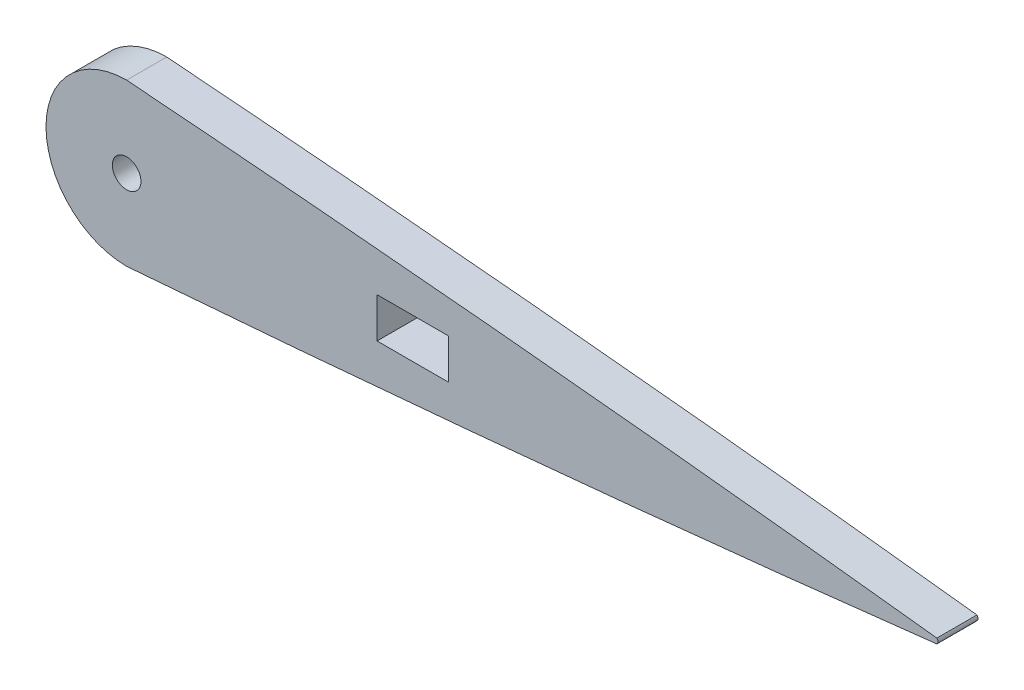
SolidWorks part; units mm, degrees
material "Фанера"
ref_plane "Front Plane" through (0, 0, 0) normal (0, 0, 1) x (1, 0, 0)
ref_plane "Top Plane" through (0, 0, 0) normal (0, 1, 0) x (1, 0, 0)
ref_plane "Right Plane" through (0, 0, 0) normal (1, 0, 0) x (0, 0, -1)
curve "Кривая1"
  spline degree 3 poles (110, 0, 0) (110.0276, -0.2367, 0) (110.0855, -0.7342, 0) (110.5302, -1.4271, 0) (111.1963, -2.0786, 0) (112.1098, -2.7013, 0) (113.2568, -3.2993, 0) (114.6379, -3.8731, 0) (116.2477, -4.4214, 0) (118.0813, -4.9426, 0) (120.1331, -5.4348, 0) (122.3972, -5.8961, 0) (124.8672, -6.3247, 0) (127.537, -6.7187, 0) (130.3997, -7.0764, 0) (133.4488, -7.3965, 0) (136.6771, -7.6776, 0) (140.0777, -7.9187, 0) (143.6433, -8.119, 0) (147.3662, -8.278, 0) (151.2389, -8.3955, 0) (155.2534, -8.4715, 0) (159.4016, -8.5065, 0) (163.6751, -8.501, 0) (168.0653, -8.456, 0) (172.5632, -8.3725, 0) (177.1595, -8.252, 0) (181.8446, -8.096, 0) (186.6087, -7.9062, 0) (191.4413, -7.6846, 0) (196.3316, -7.4331, 0) (201.2684, -7.1538, 0) (206.2396, -6.8489, 0) (211.233, -6.5205, 0) (216.2352, -6.1709, 0) (221.2323, -5.8022, 0) (226.2093, -5.417, 0) (231.1504, -5.0174, 0) (236.0382, -4.6058, 0) (240.8542, -4.1849, 0) (245.5777, -3.7574, 0) (250.1862, -3.3262, 0) (254.6542, -2.8948, 0) (258.9526, -2.4672, 0) (263.0477, -2.0479, 0) (266.899, -1.6426, 0) (270.4558, -1.2586, 0) (273.6512, -0.9053, 0) (276.3854, -0.5964, 0) (278.4526, -0.359, 0) (279.592, -0.2261, 0) (280, -0.1785, 0) knots 0 0 0 0 0.004099 0.008615 0.013935 0.020278 0.027753 0.03641 0.046266 0.05732 0.069559 0.082963 0.097507 0.113164 0.129903 0.14769 0.166492 0.186272 0.206992 0.228612 0.251092 0.274389 0.298458 0.323254 0.348728 0.37483 0.401509 0.42871 0.456376 0.484448 0.512864 0.541558 0.570462 0.599504 0.628607 0.65769 0.686667 0.715445 0.743924 0.771995 0.79954 0.826428 0.852512 0.877624 0.901571 0.924121 0.944989 0.963804 0.980044 0.992855 1 1 1 1
curve "Кривая2"
  spline degree 3 poles (280, 0.1785, 0) (279.592, 0.2261, 0) (278.4526, 0.359, 0) (276.3854, 0.5964, 0) (273.6512, 0.9053, 0) (270.4558, 1.2586, 0) (266.899, 1.6426, 0) (263.0477, 2.0479, 0) (258.9526, 2.4672, 0) (254.6542, 2.8948, 0) (250.1862, 3.3262, 0) (245.5777, 3.7574, 0) (240.8542, 4.1849, 0) (236.0382, 4.6058, 0) (231.1504, 5.0174, 0) (226.2093, 5.417, 0) (221.2323, 5.8022, 0) (216.2352, 6.1709, 0) (211.233, 6.5205, 0) (206.2396, 6.8489, 0) (201.2684, 7.1538, 0) (196.3316, 7.4331, 0) (191.4413, 7.6846, 0) (186.6087, 7.9062, 0) (181.8446, 8.096, 0) (177.1595, 8.252, 0) (172.5632, 8.3725, 0) (168.0653, 8.456, 0) (163.6751, 8.501, 0) (159.4016, 8.5065, 0) (155.2534, 8.4715, 0) (151.2389, 8.3955, 0) (147.3662, 8.278, 0) (143.6433, 8.119, 0) (140.0777, 7.9187, 0) (136.6771, 7.6776, 0) (133.4488, 7.3965, 0) (130.3997, 7.0764, 0) (127.537, 6.7187, 0) (124.8672, 6.3247, 0) (122.3972, 5.8961, 0) (120.1331, 5.4348, 0) (118.0813, 4.9426, 0) (116.2477, 4.4214, 0) (114.6379, 3.8731, 0) (113.2568, 3.2993, 0) (112.1098, 2.7013, 0) (111.1963, 2.0786, 0) (110.5302, 1.4271, 0) (110.0855, 0.7342, 0) (110.0276, 0.2367, 0) (110, 0, 0) knots 0 0 0 0 0.007145 0.019956 0.036196 0.055011 0.075879 0.098429 0.122376 0.147488 0.173572 0.20046 0.228005 0.256076 0.284555 0.313333 0.34231 0.371393 0.400496 0.429538 0.458442 0.487136 0.515552 0.543624 0.57129 0.598491 0.62517 0.651272 0.676746 0.701542 0.725611 0.748908 0.771388 0.793008 0.813728 0.833508 0.85231 0.870097 0.886836 0.902493 0.917037 0.930441 0.94268 0.953734 0.96359 0.972247 0.979722 0.986065 0.991385 0.995901 1 1 1 1
sketch "Эскиз1" plane through (0, 0, 0) normal (0, 0, 1) x (1, 0, 0)
  line L0 (105.1708, 0) -> (280.7263, 0) construction
  line L1 (280.0739, 0) -> (280.0739, 24.3846) construction
  line L2 (110, -5.3315) -> (110, 17.5304) construction
  line L3 (152.5185, 18.8331) -> (152.5185, -21.3473) construction
  line L4 (223.3826, 13.2402) -> (223.3826, -18.4275) construction
  line L5 (217.7476, 6.0581) -> (217.7476, -6.0581)
  line L6 (127.0185, -3) -> (140.0185, -3)
  line L7 (125.0185, -1) -> (125.0185, 1)
  line L8 (127.0185, 3) -> (140.0185, 3)
  line L9 (142.0185, -1) -> (142.0185, 1)
  line L10 (125.0185, -3) -> (142.0185, 3) construction
  line L11 (125.0185, 3) -> (142.0185, -3) construction
  line L12 (165.0185, -4.5) -> (185.0185, -4.5)
  line L13 (163.0185, -2.5) -> (163.0185, 2.5)
  line L14 (165.0185, 4.5) -> (185.0185, 4.5)
  line L15 (187.0185, -2.5) -> (187.0185, 2.5)
  line L16 (163.0185, -4.5) -> (187.0185, 4.5) construction
  line L17 (163.0185, 4.5) -> (187.0185, -4.5) construction
  line L18 (243.3826, 16.1127) -> (243.3826, -19.2013) construction
  line L19 (240.8826, -1.4) -> (245.8826, -1.4)
  line L20 (240.8826, -1.4) -> (240.8826, 1.4)
  line L21 (240.8826, 1.4) -> (245.8826, 1.4)
  line L22 (245.8826, -1.4) -> (245.8826, 1.4)
  line L23 (240.8826, -1.4) -> (245.8826, 1.4) construction
  line L24 (240.8826, 1.4) -> (245.8826, -1.4) construction
  arc A0 (280, 0.1785) -> (280, -0.1785) centre (279.8215, 0) cw
  circle A1 centre (152.5185, 0) radius 4
  circle A2 centre (197.5185, 0) radius 4
  arc A3 (185.0185, 4.5) -> (187.0185, 2.5) centre (185.0185, 2.5) cw
  arc A4 (185.0185, -4.5) -> (187.0185, -2.5) centre (185.0185, -2.5) ccw
  arc A5 (165.0185, -4.5) -> (163.0185, -2.5) centre (165.0185, -2.5) cw
  arc A6 (163.0185, 2.5) -> (165.0185, 4.5) centre (165.0185, 2.5) cw
  arc A7 (125.0185, 1) -> (127.0185, 3) centre (127.0185, 1) cw
  arc A8 (127.0185, -3) -> (125.0185, -1) centre (127.0185, -1) cw
  arc A9 (140.0185, -3) -> (142.0185, -1) centre (140.0185, -1) ccw
  arc A10 (140.0185, 3) -> (142.0185, 1) centre (140.0185, 1) cw
  arc A11 (223.3826, 5.635) -> (223.3826, -5.635) centre (223.3826, 0) ccw
  circle A12 centre (223.3826, 0) radius 1
  spline S0 degree 3 poles (-1802.3351, -584.8827) (164.5267, 33.7772) (105.6543, 6.1699) (110.5302, -1.4271) (111.1963, -2.0786) (112.1098, -2.7013) (113.2568, -3.2993) (114.6379, -3.8731) (116.2477, -4.4214) (118.0813, -4.9426) (120.1331, -5.4348) (122.3972, -5.8961) (124.8672, -6.3247) (127.537, -6.7187) (130.3997, -7.0764) (133.4488, -7.3965) (136.6771, -7.6776) (140.0777, -7.9187) (143.6433, -8.119) (147.3662, -8.278) (151.2389, -8.3955) (155.2534, -8.4715) (159.4016, -8.5065) (163.6751, -8.501) (168.0653, -8.456) (172.5632, -8.3725) (177.1595, -8.252) (181.8446, -8.096) (186.6087, -7.9062) (191.4413, -7.6846) (196.3316, -7.4331) (201.2684, -7.1538) (206.2396, -6.8489) (211.233, -6.5205) (216.2352, -6.1709) (221.2323, -5.8022) (226.2093, -5.417) (231.1504, -5.0174) (236.0382, -4.6058) (240.8542, -4.1849) (247.0711, -3.6222) (253.1161, -3.0479) (258.9526, -2.4672) (263.0477, -2.0479) (266.899, -1.6426) (270.4558, -1.2586) (273.6512, -0.9053) (276.3854, -0.5964) (359.5279, 8.955) (440.5611, 28.5776) (751.5392, -1938.3855) knots -0.13886 -0.13886 -0.13886 -0.13886 0.004099 0.008615 0.013935 0.020278 0.027753 0.03641 0.046266 0.05732 0.069559 0.082963 0.097507 0.113164 0.129903 0.14769 0.166492 0.186272 0.206992 0.228612 0.251092 0.274389 0.298458 0.323254 0.348728 0.37483 0.401509 0.42871 0.456376 0.484448 0.512864 0.541558 0.570462 0.599504 0.628607 0.65769 0.686667 0.715445 0.743924 0.771995 0.79954 0.852512 0.877624 0.901571 0.924121 0.944989 0.963804 0.980044 0.992855 2.419626 2.419626 2.419626 2.419626 only from (110, 0) to (280, -0.1785) construction
  spline S1 degree 3 poles (751.5383, 1938.3796) (440.561, -28.5775) (359.5279, -8.955) (276.3854, 0.5964) (273.6512, 0.9053) (270.4558, 1.2586) (266.899, 1.6426) (263.0477, 2.0479) (258.9526, 2.4672) (253.1161, 3.0479) (247.0711, 3.6222) (240.8542, 4.1849) (236.0382, 4.6058) (231.1504, 5.0174) (226.2093, 5.417) (221.2323, 5.8022) (216.2352, 6.1709) (211.233, 6.5205) (206.2396, 6.8489) (201.2684, 7.1538) (196.3316, 7.4331) (191.4413, 7.6846) (186.6087, 7.9062) (181.8446, 8.096) (177.1595, 8.252) (172.5632, 8.3725) (168.0653, 8.456) (163.6751, 8.501) (159.4016, 8.5065) (155.2534, 8.4715) (151.2389, 8.3955) (147.3662, 8.278) (143.6433, 8.119) (140.0777, 7.9187) (136.6771, 7.6776) (133.4488, 7.3965) (130.3997, 7.0764) (127.537, 6.7187) (124.8672, 6.3247) (122.3972, 5.8961) (120.1331, 5.4348) (118.0813, 4.9426) (116.2477, 4.4214) (114.6379, 3.8731) (113.2568, 3.2993) (112.1098, 2.7013) (111.1963, 2.0786) (110.5302, 1.4271) (105.6546, -6.1694) (164.5198, -33.7739) (-1801.974, 584.7691) knots -1.419625 -1.419625 -1.419625 -1.419625 0.007145 0.019956 0.036196 0.055011 0.075879 0.098429 0.122376 0.147488 0.20046 0.228005 0.256076 0.284555 0.313333 0.34231 0.371393 0.400496 0.429538 0.458442 0.487136 0.515552 0.543624 0.57129 0.598491 0.62517 0.651272 0.676746 0.701542 0.725611 0.748908 0.771388 0.793008 0.813728 0.833508 0.85231 0.870097 0.886836 0.902493 0.917037 0.930441 0.94268 0.953734 0.96359 0.972247 0.979722 0.986065 0.991385 0.995901 1.138851 1.138851 1.138851 1.138851 only from (280, 0.1785) to (110, 0) construction
  spline S2 degree 3 poles (110, 0) (110.0276, -0.2367) (110.0855, -0.7342) (110.5302, -1.4271) (111.1963, -2.0786) (112.1098, -2.7013) (113.2568, -3.2993) (114.6379, -3.8731) (116.2477, -4.4214) (118.0813, -4.9426) (120.1331, -5.4348) (122.3972, -5.8961) (124.8672, -6.3247) (127.537, -6.7187) (130.3997, -7.0764) (133.4488, -7.3965) (136.6771, -7.6776) (140.0777, -7.9187) (143.6433, -8.119) (147.3662, -8.278) (151.2389, -8.3955) (155.2534, -8.4715) (159.4016, -8.5065) (163.6751, -8.501) (168.0653, -8.456) (172.5632, -8.3725) (177.1595, -8.252) (181.8446, -8.096) (186.6087, -7.9062) (191.4413, -7.6846) (196.3316, -7.4331) (201.2684, -7.1538) (206.2396, -6.8489) (211.233, -6.5205) (216.2352, -6.1709) (221.2323, -5.8022) (226.2093, -5.417) (231.1504, -5.0174) (236.0382, -4.6058) (240.8542, -4.1849) (247.0711, -3.6222) (253.1161, -3.0479) (258.9526, -2.4672) (263.0477, -2.0479) (266.899, -1.6426) (270.4558, -1.2586) (273.6512, -0.9053) (276.3854, -0.5964) (278.4526, -0.359) (279.592, -0.2261) (280, -0.1785) knots 0 0 0 0 0.004099 0.008615 0.013935 0.020278 0.027753 0.03641 0.046266 0.05732 0.069559 0.082963 0.097507 0.113164 0.129903 0.14769 0.166492 0.186272 0.206992 0.228612 0.251092 0.274389 0.298458 0.323254 0.348728 0.37483 0.401509 0.42871 0.456376 0.484448 0.512864 0.541558 0.570462 0.599504 0.628607 0.65769 0.686667 0.715445 0.743924 0.771995 0.79954 0.852512 0.877624 0.901571 0.924121 0.944989 0.963804 0.980044 0.992855 1 1 1 1
  spline S3 degree 3 poles (280, 0.1785) (279.592, 0.2261) (278.4526, 0.359) (276.3854, 0.5964) (273.6512, 0.9053) (270.4558, 1.2586) (266.899, 1.6426) (263.0477, 2.0479) (258.9526, 2.4672) (253.1161, 3.0479) (247.0711, 3.6222) (240.8542, 4.1849) (236.0382, 4.6058) (231.1504, 5.0174) (226.2093, 5.417) (221.2323, 5.8022) (216.2352, 6.1709) (211.233, 6.5205) (206.2396, 6.8489) (201.2684, 7.1538) (196.3316, 7.4331) (191.4413, 7.6846) (186.6087, 7.9062) (181.8446, 8.096) (177.1595, 8.252) (172.5632, 8.3725) (168.0653, 8.456) (163.6751, 8.501) (159.4016, 8.5065) (155.2534, 8.4715) (151.2389, 8.3955) (147.3662, 8.278) (143.6433, 8.119) (140.0777, 7.9187) (136.6771, 7.6776) (133.4488, 7.3965) (130.3997, 7.0764) (127.537, 6.7187) (124.8672, 6.3247) (122.3972, 5.8961) (120.1331, 5.4348) (118.0813, 4.9426) (116.2477, 4.4214) (114.6379, 3.8731) (113.2568, 3.2993) (112.1098, 2.7013) (111.1963, 2.0786) (110.5302, 1.4271) (110.0855, 0.7342) (110.0276, 0.2367) (110, 0) knots 0 0 0 0 0.007145 0.019956 0.036196 0.055011 0.075879 0.098429 0.122376 0.147488 0.20046 0.228005 0.256076 0.284555 0.313333 0.34231 0.371393 0.400496 0.429538 0.458442 0.487136 0.515552 0.543624 0.57129 0.598491 0.62517 0.651272 0.676746 0.701542 0.725611 0.748908 0.771388 0.793008 0.813728 0.833508 0.85231 0.870097 0.886836 0.902493 0.917037 0.930441 0.94268 0.953734 0.96359 0.972247 0.979722 0.986065 0.991385 0.995901 1 1 1 1
  point P19 (175.0185, 0)
  point P22 (133.5185, 0)
  point P31 (223.3826, -5.635)
  point P54 (223.3826, 5.635)
  point P55 (223.3826, -5.635)
  point P56 (223.3826, 5.635)
  point P63 (243.3826, 0)
  dimension "D1" = 0.2524
  dimension "D3" = 8
  dimension "D13" = 2
  dimension "D14" = 5.635
  dimension "D15" = 2
  dimension "D2" = 170.0739
  dimension "D4" = 42.5185
  dimension "D5" = 56.6913
  dimension "D6" = 45
  dimension "D7" = 6
  dimension "D8" = 17
  dimension "D9" = 19
  dimension "D10" = 22.5
  dimension "D11" = 9
  dimension "D12" = 24
  dimension "D16" = 2.8
  dimension "D17" = 5
  dimension "D18" = 20
extrude "Бобышка-Вытянуть1" add sketch "Эскиз1" along normal mid plane 2.8 contours A0 S3 A11 S2 A12
equation "\"D4@Эскиз1\"=\"D2@Эскиз1\"/4"
equation "\"D5@Эскиз1\"=\"D2@Эскиз1\"/3"
equation "\"D10@Эскиз1\"=\"D6@Эскиз1\"/2"
